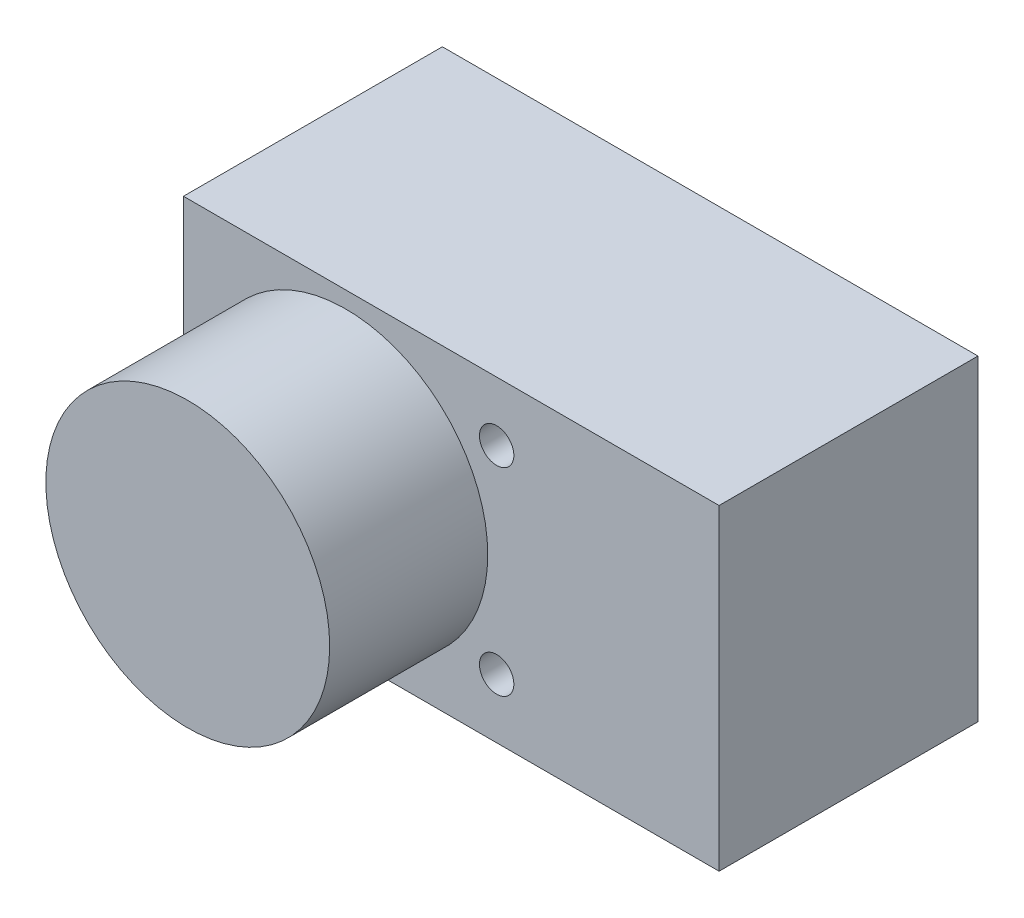
SolidWorks part; units mm, degrees
ref_plane "Front Plane" through (0, 0, 0) normal (0, 0, 1) x (1, 0, 0)
ref_plane "Top Plane" through (0, 0, 0) normal (0, 1, 0) x (1, 0, 0)
ref_plane "Right Plane" through (0, 0, 0) normal (1, 0, 0) x (0, 0, -1)
sketch "Sketch1" plane through (0, 0, 0) normal (0, 0, 1) x (1, 0, 0)
  line L1 (0, 0) -> (45.8724, 0)
  line L2 (0, 0) -> (0, 27.1272)
  line L3 (0, 27.1272) -> (45.8724, 27.1272)
  line L4 (45.8724, 0) -> (45.8724, 27.1272)
  dimension "D1" = 45.8724
  dimension "D2" = 27.1272
extrude "Boss-Extrude1" add sketch "Sketch1" along normal blind 22.1742
sketch "Sketch2" plane through (0, 0, 22.1742) normal (0, 0, 1) x (1, 0, 0)
  line L0 (0, 27.1272) -> (0, 0) construction
  line L2 (0, 13.5636) -> (45.8724, 13.5636) construction
  line L3 (45.8724, 0) -> (45.8724, 27.1272) construction
  circle A0 centre (13.9065, 13.5636) radius 12.1539
  dimension "D1" = 24.3078
  dimension "D2" = 13.9065
  dimension "D3" = 0
extrude "Boss-Extrude2" add sketch "Sketch2" along normal blind 13.5382
sketch "Sketch3" plane through (0, 0, 0) normal (0, 0, -1) x (-1, 0, 0)
  line L0 (-45.8724, 13.5636) -> (0, 13.5636) construction
  line L1 (-45.8724, 0) -> (-45.8724, 27.1272) construction
  line L2 (0, 27.1272) -> (0, 0) construction
  circle A0 centre (-11.2522, 13.5636) radius 8.9662
  dimension "D2" = 17.9324
  dimension "D3" = 11.2522
extrude "Boss-Extrude3" add sketch "Sketch3" along normal blind 1.2954 contours A0
sketch "Sketch4" plane through (0, 0, -1.2954) normal (0, 0, -1) x (-1, 0, 0)
  line L0 (-13.791, 15.8496) -> (-8.7134, 15.8496)
  line L1 (-45.8724, 13.5636) -> (0, 13.5636) construction
  line L2 (-45.8724, 0) -> (-45.8724, 27.1272) construction
  line L3 (0, 27.1272) -> (0, 0) construction
  line L4 (-13.791, 11.2776) -> (-8.7134, 11.2776)
  circle A0 centre (-11.2522, 13.5636) radius 8.9662 construction
  circle A1 centre (-11.2522, 13.5636) radius 8.9662 construction
  circle A2 centre (-11.2522, 13.5636) radius 3.4163
  dimension "D1" = 6.8326
  dimension "D2" = 2.286
extrude "Boss-Extrude4" add sketch "Sketch4" along normal blind 5.715 contours L0 A2 L4
sketch "Sketch5" plane through (0, 0, 0) normal (0, 0, -1) x (-1, 0, 0)
  line L0 (0, 0) -> (-45.8724, 0) construction
  line L1 (-45.8724, 27.1272) -> (0, 27.1272) construction
  line L2 (-45.8724, 0) -> (-45.8724, 27.1272) construction
  point P0 (-26.8224, 22.0472)
  point P1 (-26.8224, 5.08)
  dimension "D1" = 5.08
  dimension "D2" = 5.08
  dimension "D3" = 19.05
  dimension "D4" = 0
hole_wizard "#32 (0.116) Diameter Hole1" positions "Sketch6" profile "Sketch7" hole size "#32" standard "ANSI Inch" end condition through all
sketch "Sketch6" plane through (0, 0, 0) normal (0, 0, -1) x (-1, 0, 0)
  point P0 (-26.8224, 22.0472)
  point P3 (-26.8224, 5.08)
sketch "Sketch7" plane through (26.8224, 22.0472, 0) normal (1, 0, 0) x (0, 1, 0)
  line L0 (0, 0) -> (0, 35.7124)
  line L1 (0, 35.7124) -> (1.4732, 35.7124)
  line L2 (1.4732, 35.7124) -> (1.4732, 0)
  line L5 (1.4732, 0) -> (0, 0)
  line L11 (0, -6.35) -> (0, 107.95) construction
  dimension "Thru Hole Dia." = 2.9464
  dimension "Thru Hole Depth" = 35.7124
sketch "Sketch8" plane through (0, 0, -1.2954) normal (0, 0, -1) x (-1, 0, 0)
  circle A0 centre (-26.8224, 5.08) radius 1.4732 construction
  circle A1 centre (-26.8224, 22.0472) radius 1.4732 construction
  circle A2 centre (-11.2522, 13.5636) radius 8.9662 construction
  circle A3 centre (-26.8224, 5.08) radius 1.4732
  circle A4 centre (-26.8224, 22.0472) radius 1.4732
  circle A5 centre (-11.2522, 13.5636) radius 8.9662
  dimension "D1" = 15.5702
  dimension "D2" = 8.4836
equation "\"height\"= 0.051"
equation "\"diameter\"= .269"
equation "\"D1@Boss-Extrude3\"=\"height\""
equation "\"D1@Sketch4\"=\"diameter\""
equation "\"holefromwall\"= .2"
